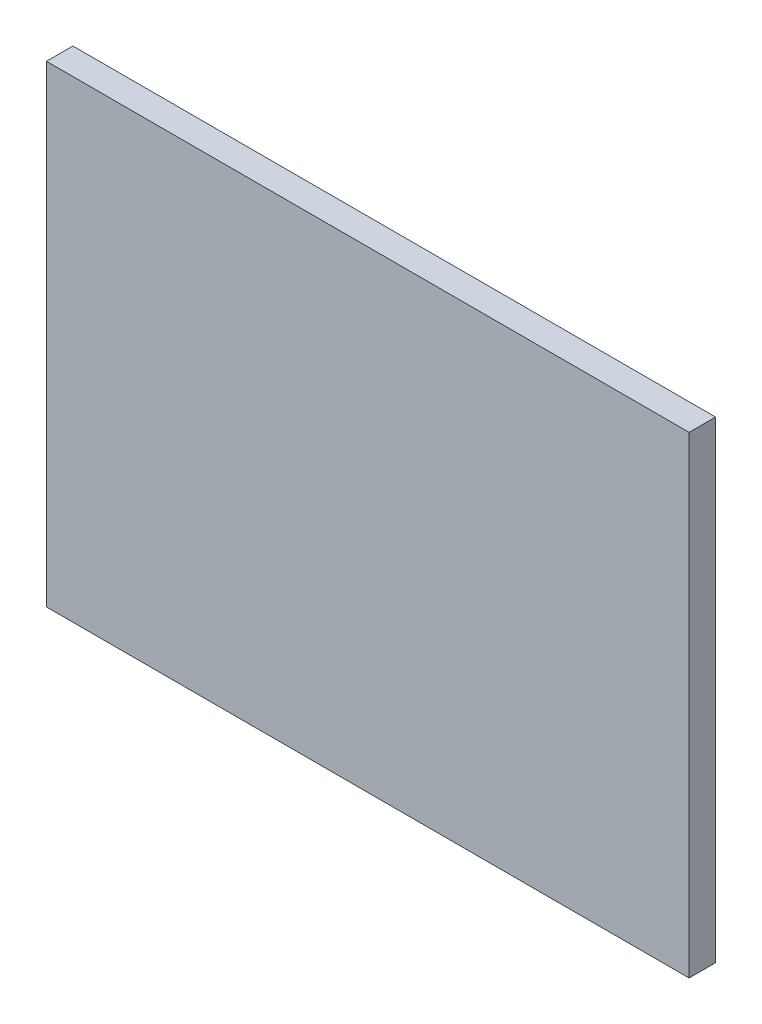
SolidWorks part; units mm, degrees
ref_plane "前视" through (0, 0, 0) normal (0, 0, 1) x (1, 0, 0)
ref_plane "上视" through (0, 0, 0) normal (0, 1, 0) x (1, 0, 0)
ref_plane "右视" through (0, 0, 0) normal (1, 0, 0) x (0, 0, -1)
sketch "草图1" plane through (0, 0, 0) normal (0, 0, 1) x (1, 0, 0)
  line L1 (-170, 125) -> (170, 125)
  line L2 (-170, 125) -> (-170, -125)
  line L3 (-170, -125) -> (170, -125)
  line L4 (170, 125) -> (170, -125)
  line L5 (-120, 169.1177) -> (-120, -68.0463) construction
  dimension "D1" = 250
  dimension "D2" = 340
  dimension "D4" = 50
extrude "基体-拉伸" add sketch "草图1" along normal blind 14
